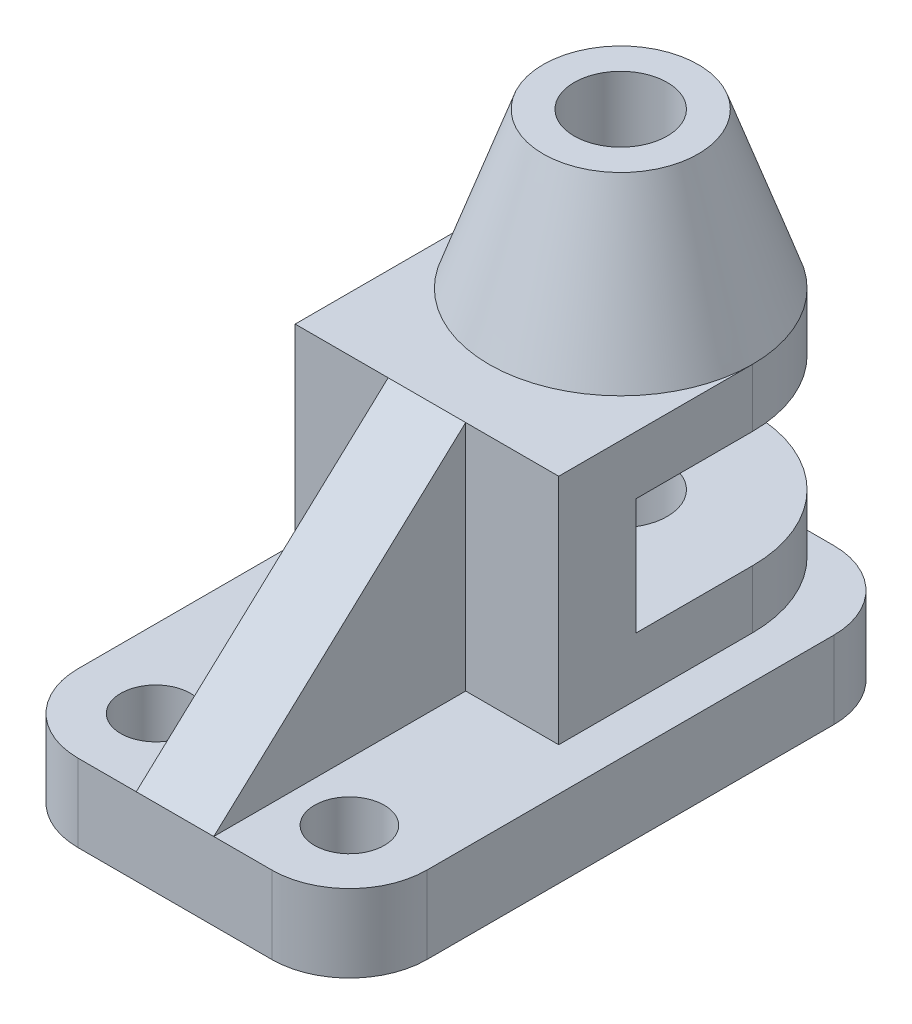
SolidWorks part; units mm, degrees
ref_plane "Front Plane" through (0, 0, 0) normal (0, 0, 1) x (1, 0, 0)
ref_plane "Top Plane" through (0, 0, 0) normal (0, 1, 0) x (1, 0, 0)
ref_plane "Right Plane" through (0, 0, 0) normal (1, 0, 0) x (0, 0, -1)
sketch "Sketch1" plane through (0, 0, 0) normal (0, 1, 0) x (1, 0, 0)
  line L5 (-45, -72.5) -> (45, 72.5) construction
  line L6 (-45, 72.5) -> (45, -72.5) construction
  line L7 (45, -72.5) -> (-45, -72.5)
  line L8 (45, -72.5) -> (45, 72.5)
  line L9 (45, 72.5) -> (-45, 72.5)
  line L10 (-45, -72.5) -> (-45, 72.5)
  line L11 (45, -72.5) -> (-45, 72.5) construction
  line L12 (45, 72.5) -> (-45, -72.5) construction
  point P0 (0, 0)
  point P6 (0, 0)
  dimension "D1" = 145
  dimension "D2" = 90
extrude "Boss-Extrude2" add sketch "Sketch1" along normal mid plane 20
ref_plane "Plane5" through (0, 0, 7.5) normal (0, 0, 1) x (1, 0, 0)
ref_plane "Plane6" through (0, 0, 0) normal (1, 0, 0) x (0, 0, -1)
fillet "Fillet2" radius 20 4 edges at (45, 0, -72.5) (-45, 0, -72.5) (45, 0, 72.5) (-45, 0, 72.5)
sketch "Sketch8" plane through (0, 10, 0) normal (0, 1, 0) x (1, 0, 0)
  line L0 (-34, -7.5) -> (-34, 42.5)
  line L1 (-11, -7.5) -> (11, -7.5) construction
  line L2 (34, -7.5) -> (34, 42.5)
  line L3 (-34, -7.5) -> (34, -7.5)
  arc A0 (34, 42.5) -> (-34, 42.5) centre (0, 42.5) ccw
  dimension "D1" = 68
  dimension "D2" = 50
extrude "Boss-Extrude6" add sketch "Sketch8" along normal blind 60
sketch "Sketch9" plane through (0, 70, 0) normal (0, 1, 0) x (1, 0, 0)
  line L0 (-34, 12.5) -> (34, 12.5)
  line L1 (-34, 42.5) -> (-34, -7.5) construction
  line L2 (34, -7.5) -> (34, 42.5) construction
  line L3 (-11, -7.5) -> (11, -7.5) construction
  line L7 (-34, -7.5) -> (34, -7.5)
  line L8 (34, -7.5) -> (34, 42.5)
  line L9 (-34, 42.5) -> (-34, -7.5)
  line L10 (-34, -7.5) -> (34, -7.5)
  line L11 (34, -7.5) -> (34, 42.5)
  line L12 (-34, 42.5) -> (-34, -7.5)
  arc A1 (34, 42.5) -> (-34, 42.5) centre (0, 42.5) ccw
  arc A2 (34, 42.5) -> (-34, 42.5) centre (0, 42.5) ccw
  line M7 (34, -7.5) -> (34, 42.5)
  arc M8 (34, 42.5) -> (-34, 42.5) centre (0, 42.5) ccw
  line M9 (-34, 42.5) -> (-34, -7.5)
  dimension "D1" = 20
  dimension "D2" = 0
extrude "Cut-Extrude1" cut sketch "Sketch9" against normal blind 30 from offset 15 contours L0 M9 M7 M8 offset against normal yes
ref_plane "Plane7" through (0, 0, -42.5) normal (0, 0, 1) x (1, 0, 0)
sketch "Sketch12" plane through (0, 0, -42.5) normal (0, 0, 1) x (1, 0, 0)
  line L0 (0, 70) -> (0, 110)
  line L1 (-34, 70) -> (34, 70) construction
  line L2 (0, 70) -> (0, 55) construction
  line L3 (0, 110) -> (20, 110)
  line L4 (20, 110) -> (34, 70)
  line L5 (34, 70) -> (-34, 70) construction
  line L6 (34, 70) -> (0, 70)
  point P7 (0, 0)
  point P12 (0, 0)
  dimension "D1" = 20
  dimension "D2" = 40
revolve "Revolve1" add sketch "Sketch12" angle 360 about L0
sketch "Sketch13" plane through (0, 110, 0) normal (0, 1, 0) x (1, 0, 0)
  circle A0 centre (0, 42.5) radius 12
  dimension "D1" = 24
extrude "Cut-Extrude2" cut sketch "Sketch13" against normal blind 127
sketch "Sketch16" plane through (0, 0, 0) normal (1, 0, 0) x (0, 0, -1)
  line L0 (-7.5, 70) -> (-72.5, 10)
  line L1 (-72.5, -10) -> (-72.5, 10) construction
  line L2 (-52.5, 10) -> (-72.5, 10) construction
  line L3 (-7.5, 70) -> (-7.5, 10) construction
  line L4 (-7.5, 70) -> (-7.5, 10)
  line L5 (-72.5, 10) -> (-7.5, 10)
extrude "Boss-Extrude8" add sketch "Sketch16" along normal mid plane 20
sketch "Sketch17" plane through (0, 10, 0) normal (0, 1, 0) x (1, 0, 0)
  line L0 (45, -52.5) -> (-45, -52.5) construction
  line L1 (25, -72.5) -> (25, -35.7819) construction
  circle A0 centre (25, -52.5) radius 9
  dimension "D1" = 18
extrude "Cut-Extrude3" cut sketch "Sketch17" against normal blind 20 contours A0
mirror "Mirror1" about plane through (0, 0, 0) normal (1, 0, 0) of "Cut-Extrude3"
